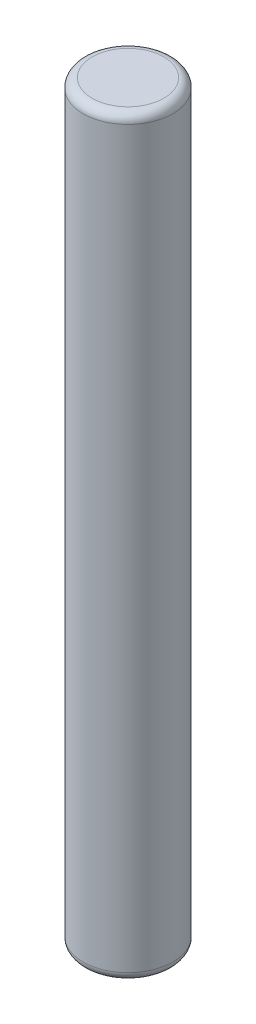
SolidWorks part; units mm, degrees
ref_plane "前视基准面" through (0, 0, 0) normal (0, 0, 1) x (1, 0, 0)
ref_plane "上视基准面" through (0, 0, 0) normal (0, 1, 0) x (1, 0, 0)
ref_plane "右视基准面" through (0, 0, 0) normal (1, 0, 0) x (0, 0, -1)
sketch "草图1" plane through (0, 0, 0) normal (0, 1, 0) x (1, 0, 0)
  circle A0 centre (0, 0) radius 2.5
  dimension "D1" = 5
extrude "凸台-拉伸1" add sketch "草图1" along normal blind 42
fillet "圆角1" radius 0.5 2 edges at (0, 0, 2.5) (0, 42, 2.5)
